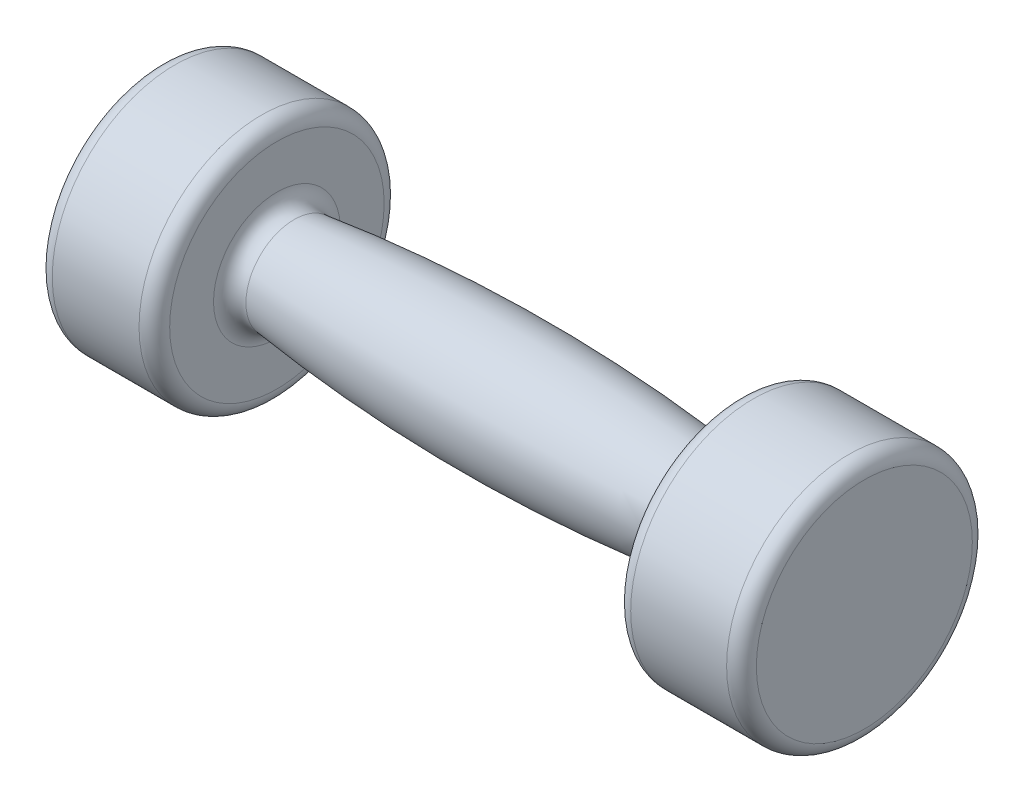
SolidWorks part; units mm, degrees
ref_plane "Front Plane" through (0, 0, 0) normal (0, 0, 1) x (1, 0, 0)
ref_plane "Top Plane" through (0, 0, 0) normal (0, 1, 0) x (1, 0, 0)
ref_plane "Right Plane" through (0, 0, 0) normal (1, 0, 0) x (0, 0, -1)
sketch "Sketch1" plane through (0, 0, 0) normal (0, 0, 1) x (1, 0, 0)
  line L0 (141.7186, 0) -> (-88.2814, 0) construction
  line L1 (-88.2814, 0) -> (-88.2814, -35.2476)
  line L2 (-83.3241, -40) -> (-55.0092, -40)
  line L3 (-50.0092, -35) -> (-50.0092, -20.6859)
  line L5 (100.5032, -35.1487) -> (100.1895, -20.4202)
  line L6 (136.7613, -40) -> (105.459, -40)
  line L7 (141.7186, 0) -> (141.7186, -35.2476)
  line L8 (26.7186, -104.1636) -> (26.7186, 0) construction
  line L10 (-88.2814, 0) -> (141.7186, 0)
  arc A0 (-88.2814, -35.2476) -> (-83.3241, -40) centre (-83.3241, -35.0383) ccw
  arc A5 (141.7186, -35.2476) -> (136.7613, -40) centre (136.7613, -35.0383) cw
  arc A6 (-44.3998, -15.7232) -> (94.5701, -15.5653) centre (24.4483, 545.0207) ccw
  arc A7 (-55.0092, -40) -> (-50.0092, -35) centre (-55.0092, -35) ccw
  arc A8 (100.5032, -35.1487) -> (105.459, -40) centre (105.459, -35.0431) ccw
  arc A9 (-44.3998, -15.7232) -> (-50.0092, -20.6859) centre (-45.0092, -20.6859) ccw
  arc A10 (100.1895, -20.4202) -> (94.5701, -15.5653) centre (95.1907, -20.5267) ccw
  point P5 (25.09, -19.9336)
  point P7 (26.7186, -15)
  point P19 (0, 0)
  point P30 (0, 0)
  point P32 (26.7186, 0)
  point P42 (26.7186, 15)
  dimension "D7" = 10
  dimension "D1" = 230
  dimension "D2" = 115
  dimension "D3" = 35.2476
  dimension "D5" = 80
  dimension "D4" = 10
  dimension "D8" = 10
  dimension "D9" = 564.9547
  dimension "D6" = 20
  dimension "D10" = 14.3141
revolve "Revolve1" add sketch "Sketch1" angle 360 about L10
